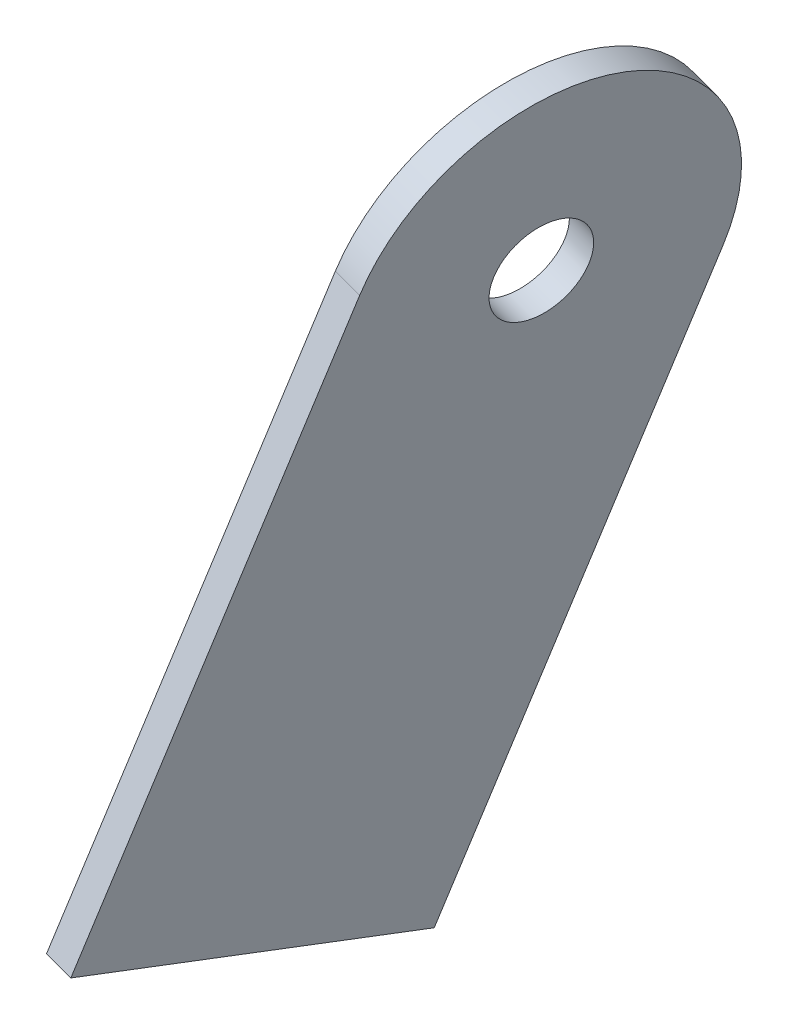
SolidWorks part; units mm, degrees
ref_plane "Front Plane" through (0, 0, 0) normal (0, 0, 1) x (1, 0, 0)
ref_plane "Top Plane" through (0, 0, 0) normal (0, 1, 0) x (1, 0, 0)
ref_plane "Right Plane" through (0, 0, 0) normal (1, 0, 0) x (0, 0, -1)
ref_plane "Plane1" through (-406.4343, 66.9882, -60.0804) normal (-0.9764, 0.1609, -0.1443) x (-0.1424, 0.0235, 0.9895)
sketch "Sketch1" plane through (-406.4343, 66.9882, -60.0804) normal (-0.9764, 0.1609, -0.1443) x (-0.1424, 0.0235, 0.9895)
  line L0 (-412.2321, 215.7129) -> (-412.54, 210.108) construction
  line L1 (-412.137, 178.7985) -> (-421.5125, 210.1842)
  line L2 (-74.0304, 279.7982) -> (-458.8705, 164.8382) construction
  line L3 (-403.2595, 215.6367) -> (-393.884, 184.2511)
  line L4 (-393.884, 184.2511) -> (-412.137, 178.7985)
  arc A0 (-421.5125, 210.1842) -> (-403.2595, 215.6367) centre (-412.386, 212.9104) cw
  arc A1 (-418.8877, 268.2143) -> (-399.8664, 267.1695) centre (-409.3771, 267.6919) ccw construction
  circle A2 centre (-412.386, 212.9104) radius 2.4892
  point P4 (-412.386, 212.9104)
  dimension "D1" = 4.9784
extrude "Boss-Extrude1" add sketch "Sketch1" along normal blind 1.5875
